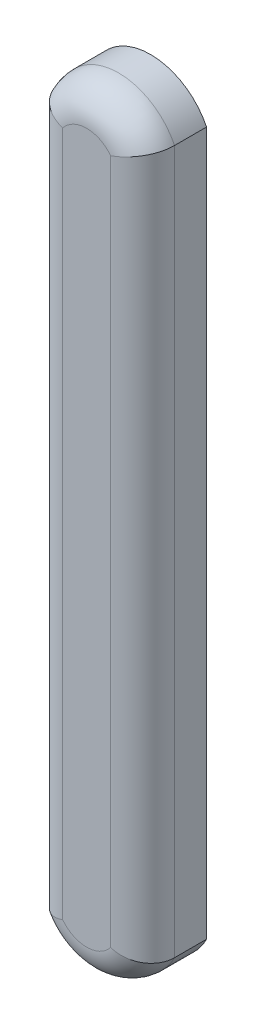
SolidWorks part; units mm, degrees
material "Plastique personnalisé"
ref_plane "Plan de face" through (0, 0, 0) normal (0, 0, 1) x (1, 0, 0)
ref_plane "Plan de dessus" through (0, 0, 0) normal (0, 1, 0) x (1, 0, 0)
ref_plane "Plan de droite" through (0, 0, 0) normal (1, 0, 0) x (0, 0, -1)
sketch "Esquisse1" plane through (0, 0, 0) normal (0, 0, 1) x (1, 0, 0)
  line L0 (0, 1.1) -> (0.35, 1.1) construction
  line L2 (0, 0) -> (0, 2.2)
  line L4 (0.35, 0) -> (0.35, 2.2)
  arc A0 (0, 2.2) -> (0.35, 2.2) centre (0.175, 2.114) cw
  arc A1 (0, 0) -> (0.35, 0) centre (0.175, 0.086) ccw
  dimension "D1" = 2.2
  dimension "D2" = 0.35
  dimension "D3" = 2.2
extrude "Boss.-Extru.1" add sketch "Esquisse1" along normal blind 0.2
fillet "Congé1" radius 0.1 4 edges at (0.175, -0.109, 0.2) (0, 1.1, 0.2) (0.35, 1.1, 0.2) (0.175, 2.309, 0.2)
